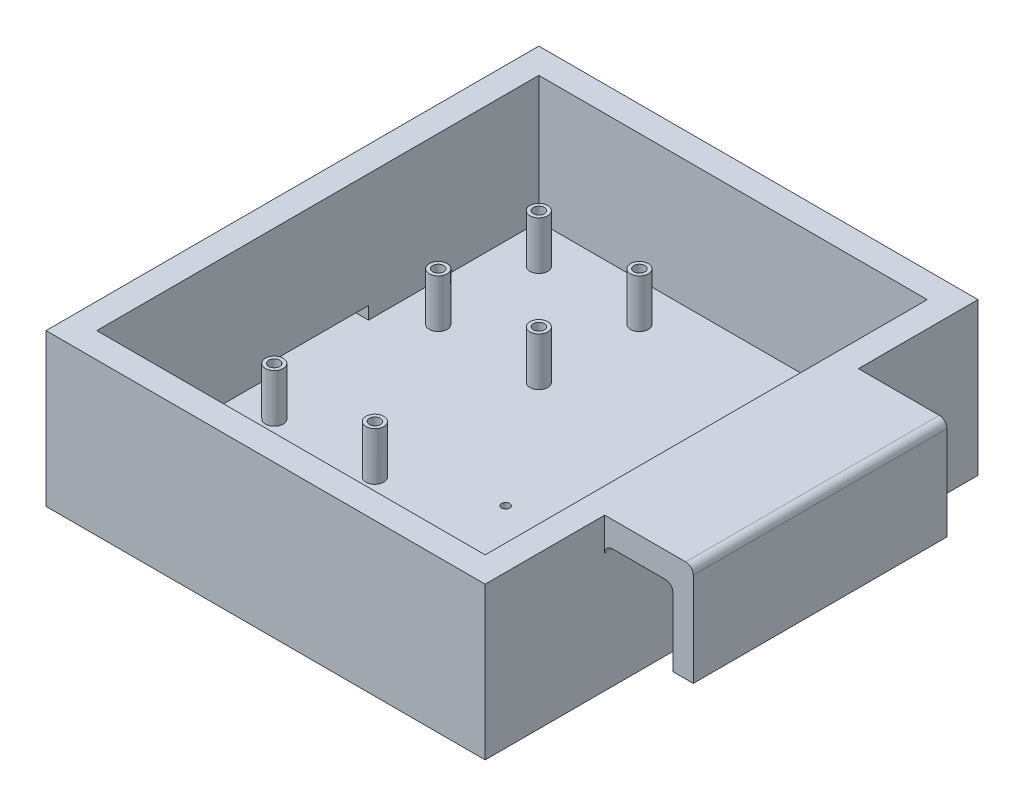
SolidWorks part; units mm, degrees
ref_plane "Alzado" through (0, 0, 0) normal (0, 0, 1) x (1, 0, 0)
ref_plane "Planta" through (0, 0, 0) normal (0, 1, 0) x (1, 0, 0)
ref_plane "Vista lateral" through (0, 0, 0) normal (1, 0, 0) x (0, 0, -1)
sketch "Croquis1" plane through (0, 0, 0) normal (0, 1, 0) x (1, 0, 0)
  line L0 (0, 0) -> (-200, 0) construction
  line L1 (-113.45, 97.1264) -> (-113.45, -97.1264) construction
  line L2 (0, -50) -> (-26.9, -50)
  line L3 (0, -50) -> (0, 50)
  line L4 (0, 50) -> (-26.9, 50)
  line L5 (-26.9, -50) -> (-26.9, 50)
  line L6 (-200, -97.1264) -> (-26.9, -97.1264)
  line L7 (-200, -97.1264) -> (-200, 97.1264)
  line L8 (-200, 97.1264) -> (-26.9, 97.1264)
  line L9 (-26.9, -97.1264) -> (-26.9, 97.1264)
  line L10 (-200, -97.1264) -> (-26.9, 97.1264) construction
  line L11 (-200, 97.1264) -> (-26.9, -97.1264) construction
  point P7 (-113.45, 0)
  point P12 (-200, 0)
  point P13 (0, 0)
  dimension "D1" = 200
  dimension "D2" = 100
  dimension "D3" = 26.9
extrude "Saliente-Extruir1" add sketch "Croquis1" along normal blind 60 contours L7 L6 L9 L8
shell "Vaciado1" thickness 10
sketch "Croquis2" plane through (0, 10, 0) normal (0, 1, 0) x (1, 0, 0)
  line L1 (-130, 27.1264) -> (-180, 27.1264)
  line L2 (-130, 27.1264) -> (-130, 77.1264)
  line L3 (-130, 77.1264) -> (-180, 77.1264)
  line L4 (-180, 27.1264) -> (-180, 77.1264)
  line L5 (-130, 27.1264) -> (-180, 77.1264) construction
  line L6 (-130, 77.1264) -> (-180, 27.1264) construction
  line L8 (-190, 87.1264) -> (-36.9, 87.1264) construction
  line L9 (-190, -87.1264) -> (-190, 87.1264) construction
  line L11 (-133, 30.1264) -> (-177, 30.1264) construction
  line L12 (-133, 30.1264) -> (-133, 74.1264) construction
  line L13 (-133, 74.1264) -> (-177, 74.1264) construction
  line L14 (-177, 30.1264) -> (-177, 74.1264) construction
  line L15 (-133, 30.1264) -> (-177, 74.1264) construction
  line L16 (-133, 74.1264) -> (-177, 30.1264) construction
  circle A0 centre (-174.835, 71.9614) radius 2.165
  circle A1 centre (-135.185, 71.9614) radius 2.165
  circle A2 centre (-135.185, 32.3114) radius 2.165
  circle A3 centre (-174.835, 32.3114) radius 2.165
  circle A4 centre (-174.835, 71.9614) radius 3.5
  circle A5 centre (-135.185, 71.9614) radius 3.5
  circle A6 centre (-174.835, 32.3114) radius 3.5
  circle A7 centre (-135.185, 32.3114) radius 3.5
  point P0 (-155, 52.1264)
  point P5 (-174.835, 74.1264)
  point P10 (-155, 52.1264)
  point P17 (-177, 71.9614)
  point P19 (-174.835, 71.9614)
  dimension "D6" = 4.33
  dimension "D9" = 7
  dimension "D10" = 7
  dimension "D1" = 50
  dimension "D2" = 50
  dimension "D3" = 10
  dimension "D4" = 10
  dimension "D5" = 3
  dimension "D7" = 2
  dimension "D8" = 2
extrude "Saliente-Extruir2" add sketch "Croquis2" along normal blind 19 contours A7 A2 | A6 A3 | A4 A0 | A5 A1
mirror "Simetría1" about plane through (0, 0, 0) normal (0, 0, 1) of "Saliente-Extruir2"
sketch "Croquis3" plane through (0, 10, 0) normal (0, 1, 0) x (1, 0, 0)
  line L0 (-190, -87.1264) -> (-36.9, -87.1264) construction
  line L9 (12.2033, 3.5744) -> (9.6633, 1.0344)
  line L10 (9.6633, 1.0344) -> (-3.2907, 1.0344)
  line L11 (-3.2907, 1.0344) -> (-3.2907, -65.0056)
  line L12 (-3.2907, -65.0056) -> (50.0493, -65.0056)
  line L13 (50.0493, -65.0056) -> (50.0493, 1.0344)
  line L14 (50.0493, 1.0344) -> (47.5093, 1.0344)
  line L15 (47.5093, 1.0344) -> (44.9693, 3.5744)
  line L16 (44.9693, 3.5744) -> (12.2033, 3.5744)
  circle A0 centre (-99.6185, -16.3264) radius 1.59
  circle A1 centre (-51.3585, -16.3264) radius 1.59
  circle A2 centre (-94.5385, -67.1264) radius 1.59
  circle A3 centre (-66.5985, -67.1264) radius 1.59
  circle A8 centre (14.4893, 1.0344) radius 1.5875
  circle A9 centre (42.4293, 1.0344) radius 1.5875
  circle A10 centre (47.5093, -51.0356) radius 1.5875
  circle A11 centre (-0.7507, -49.7656) radius 1.5875
  dimension "D1" = 48.26
  dimension "D2" = 15.24
  dimension "D3" = 50.8
  dimension "D4" = 27.94
  dimension "D5" = 3.18
  dimension "D6" = 20
extrude "Cortar-Extruir1" cut sketch "Croquis3" against normal blind 19
sketch "Croquis5" plane through (-190, 0, 0) normal (1, 0, 0) x (0, 0, -1)
  line L0 (-87.1264, 10) -> (87.1264, 10) construction
  line L1 (-20, 10) -> (20, 10)
  line L2 (-20, 10) -> (-20, 15)
  line L3 (-20, 15) -> (20, 15)
  line L4 (20, 10) -> (20, 15)
  point P6 (0, 10)
  dimension "D1" = 5
  dimension "D2" = 40
extrude "Cortar-Extruir2" cut sketch "Croquis5" against normal blind 19
sketch "Croquis6" plane through (0, 60, 0) normal (0, 1, 0) x (1, 0, 0)
  line L4 (-200, -97.1264) -> (-26.9, -97.1264)
  line L5 (-26.9, -97.1264) -> (-26.9, 97.1264)
  line L6 (-26.9, 97.1264) -> (-200, 97.1264)
  line L7 (-200, 97.1264) -> (-200, -97.1264)
  line L9 (-26.9, -50) -> (-26.9, 50)
  line L12 (-26.9, -50) -> (0, -50)
  line L13 (-26.9, 50) -> (-26.9, -50)
  line L14 (0, 50) -> (-26.9, 50)
  line L15 (0, -50) -> (0, 50)
  line L16 (-26.9, -50) -> (0, -50)
  line L17 (-26.9, 50) -> (-26.9, -50)
  line L18 (0, 50) -> (-26.9, 50)
  line L19 (0, -50) -> (0, 50)
  dimension "D1" = 0
  dimension "D2" = 0
extrude "Saliente-Extruir3" add sketch "Croquis6" against normal blind 10 contours L16 L19 L18 L17
sketch "Croquis7" plane through (0, 60, 0) normal (0, 1, 0) x (1, 0, 0)
  line L0 (-26.9, -50) -> (0, -50) construction
  line L1 (0, 50) -> (8, 50)
  line L2 (0, 50) -> (0, -50)
  line L3 (0, -50) -> (8, -50)
  line L4 (8, 50) -> (8, -50)
  dimension "D1" = 8
extrude "Saliente-Extruir4" add sketch "Croquis7" against normal blind 40
fillet "Redondeo1" radius 3 2 edges at (0, 50, 0) (-26.9, 50, 0)
fillet "Redondeo2" radius 3 1 edges at (8, 60, 0)
